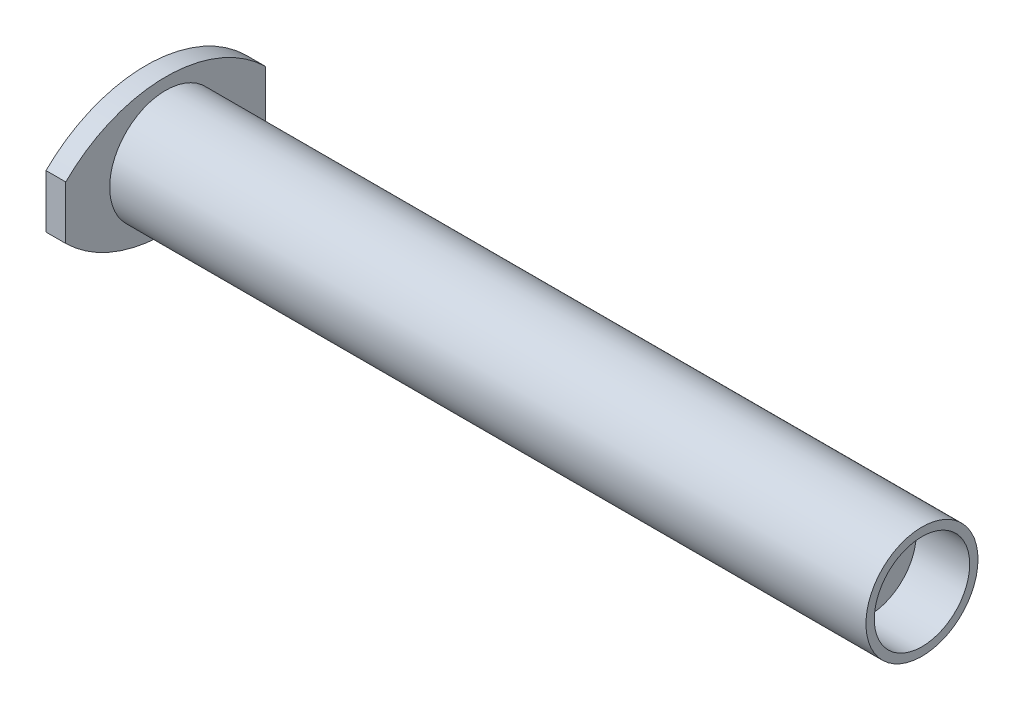
SolidWorks part; units mm, degrees
material "ABS"
ref_plane "Front Plane" through (0, 0, 0) normal (0, 0, 1) x (1, 0, 0)
ref_plane "Top Plane" through (0, 0, 0) normal (0, 1, 0) x (1, 0, 0)
ref_plane "Right Plane" through (0, 0, 0) normal (1, 0, 0) x (0, 0, -1)
sketch "Sketch1" plane through (0, 0, 0) normal (1, 0, 0) x (0, 0, -1)
  circle A0 centre (0, 0) radius 5.675
  dimension "D1" = 11.35
extrude "Boss-Extrude1" add sketch "Sketch1" against normal blind 76.6
sketch "Sketch2" plane through (-76.6, 0, 0) normal (-1, 0, 0) x (0, 0, 1)
  line L2 (-10.125, -2.7) -> (-10.125, 2.7)
  line L4 (10.125, -2.7) -> (10.125, 2.7)
  arc A1 (-10.125, 2.7) -> (10.125, 2.7) centre (0, -7.5394) cw
  arc A2 (-10.125, -2.7) -> (10.125, -2.7) centre (0, 7.5394) ccw
  dimension "D4" = 14.4
  dimension "D5" = 14.4
  dimension "D2" = 20.25
  dimension "D3" = 5.4
extrude "Boss-Extrude2" add sketch "Sketch2" along normal blind 2
sketch "Sketch3" plane through (0, 0, 0) normal (1, 0, 0) x (0, 0, -1)
  circle A0 centre (0, 0) radius 4.83
  dimension "D1" = 9.66
extrude "Cut-Extrude1" cut sketch "Sketch3" against normal through all
ref_plane "Plane1" through (-60, 0, 0) normal (-1, 0, 0) x (0, 0, 1)
sketch "Sketch4" plane through (-60, 0, 0) normal (-1, 0, 0) x (0, 0, 1)
  circle A0 centre (0, 0) radius 4.83
  circle A1 centre (0, 0) radius 1.71
  dimension "D1" = 3.42
extrude "Boss-Extrude3" add sketch "Sketch4" against normal blind 1
ref_plane "Plane2" through (-5.4, 0, 0) normal (1, 0, 0) x (0, 0, -1)
sketch "Sketch5" plane through (-5.4, 0, 0) normal (1, 0, 0) x (0, 0, -1)
  circle A0 centre (0, 0) radius 4.83
  circle A1 centre (0, 0) radius 2.4
  dimension "D1" = 4.8
extrude "Boss-Extrude4" add sketch "Sketch5" against normal blind 1
